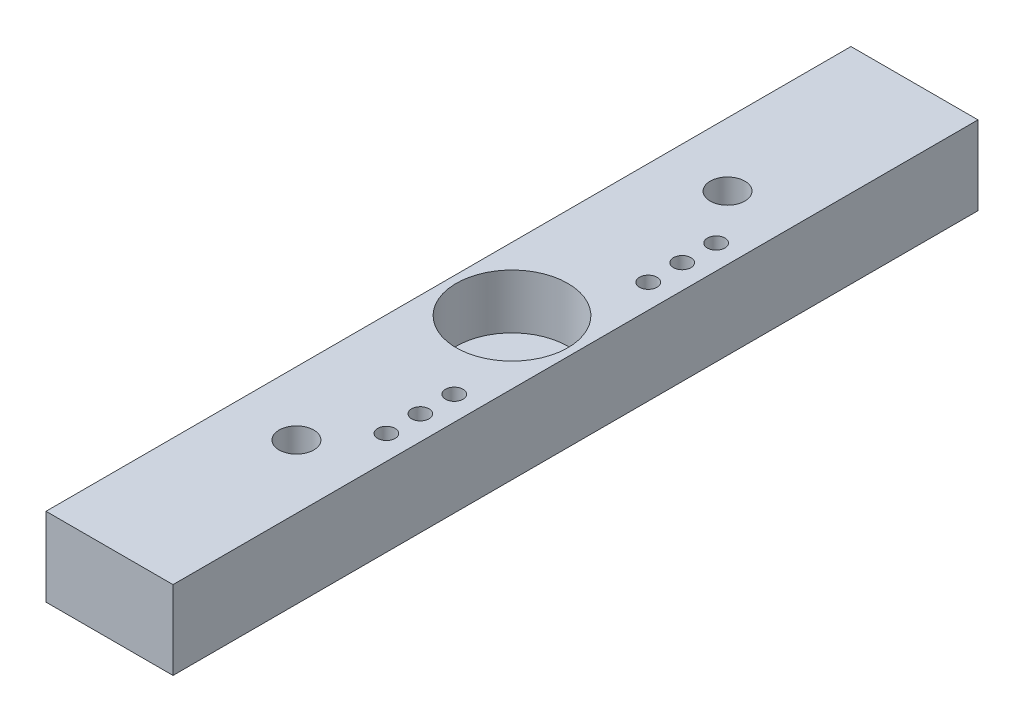
SolidWorks part; units mm, degrees
ref_plane "Front Plane" through (0, 0, 0) normal (0, 0, 1) x (1, 0, 0)
ref_plane "Top Plane" through (0, 0, 0) normal (0, 1, 0) x (1, 0, 0)
ref_plane "Right Plane" through (0, 0, 0) normal (1, 0, 0) x (0, 0, -1)
ref_plane "Plane1"
sketch "Sketch1" plane through (0, 0, 0) normal (0, 1, 0) x (-1, 0, 0)
  line L0 (19.05, 83) -> (19.05, -83)
  line L1 (19.05, -83) -> (-19.05, -83)
  line L2 (-19.05, -83) -> (-19.05, 83)
  line L3 (-19.05, 83) -> (19.05, 83)
  circle A0 centre (0, 44.45) radius 3.5719
  circle A1 centre (0, -44.45) radius 3.5719
  circle A2 centre (0, 0) radius 11.5094
  dimension "D1" = 23.0188
  dimension "D4" = 7.1437
  dimension "D5" = 7.1437
  dimension "D2" = 44.45
  dimension "D3" = 44.45
extrude "Extrusion1" add sketch "Sketch1" along normal blind 25.4 contours L3 L2 L1 L0 A2 A1 A0
sketch "Sketch2" plane through (0, 0, -83) normal (0, 0, -1) x (-1, 0, 0)
  line L0 (-19.05, 25.4) -> (19.05, 25.4)
  line L1 (19.05, 25.4) -> (19.05, 16.2292)
  line L2 (19.05, 16.2292) -> (-19.05, 16.2292)
  line L3 (-19.05, 16.2292) -> (-19.05, 25.4)
extrude "Extrusion15" cut sketch "Sketch2" against normal up to next
sketch "Sketch3" plane through (0, 16.2292, 0) normal (0, 1, 0) x (-1, 0, 0)
  line L0 (19.05, 83) -> (-19.05, 83)
  line L1 (-19.05, 83) -> (-19.05, 51.1969)
  line L2 (-19.05, 51.1969) -> (19.05, 51.1969)
  line L3 (19.05, 51.1969) -> (19.05, 83)
  line L4 (-19.05, -51.1969) -> (-19.05, -83)
  line L5 (-19.05, -83) -> (19.05, -83)
  line L6 (19.05, -83) -> (19.05, -51.1969)
  line L7 (19.05, -51.1969) -> (-19.05, -51.1969)
ref_plane "Plane2"
sketch "Sketch4" plane through (0, 25.4, 0) normal (0, 1, 0) x (1, 0, 0)
  line L0 (-19.05, -83) -> (-13.0969, -83)
  line L1 (-13.0969, -83) -> (-13.0969, 83)
  line L2 (-13.0969, 83) -> (-19.05, 83)
  line L3 (-19.05, 83) -> (-19.05, -83)
  line L4 (19.05, -83) -> (13.0969, -83)
  line L5 (13.0969, -83) -> (13.0969, 83)
  line L6 (13.0969, 83) -> (19.05, 83)
  line L7 (19.05, 83) -> (19.05, -83)
  circle A0 centre (8.0969, -34) radius 1.8
  circle A1 centre (8.0969, -27) radius 1.8
  circle A2 centre (8.0969, -20) radius 1.8
  circle A3 centre (8.0969, 20) radius 1.8
  circle A4 centre (8.0969, 27) radius 1.8
  circle A5 centre (8.0969, 34) radius 1.8
  dimension "D1" = 3.6
  dimension "D2" = 3.6
  dimension "D3" = 3.6
  dimension "D4" = 3.6
  dimension "D5" = 3.6
  dimension "D6" = 3.6
  dimension "D7" = 7
  dimension "D8" = 7
  dimension "D9" = 7
  dimension "D10" = 7
  dimension "D11" = 21.5768
  dimension "D12" = 21.5768
extrude "Extrusion18" cut sketch "Sketch4" against normal up to next contours A0 | A1 | A2 | A3 | A4 | A5 | L2 L3 L0 L1 | L7 L6 L5 L4
ref_plane "Plane3"
sketch "Sketch5" plane through (0, 0, 0) normal (0, -1, 0) x (1, 0, 0)
  circle A0 centre (0, 44.45) radius 3.5719
  circle A1 centre (0, -44.45) radius 3.5719
  circle A2 centre (0, 0) radius 11.5094
extrude "Extrusion19" add sketch "Sketch5" against normal blind 5 contours A0 | A1 | A2
